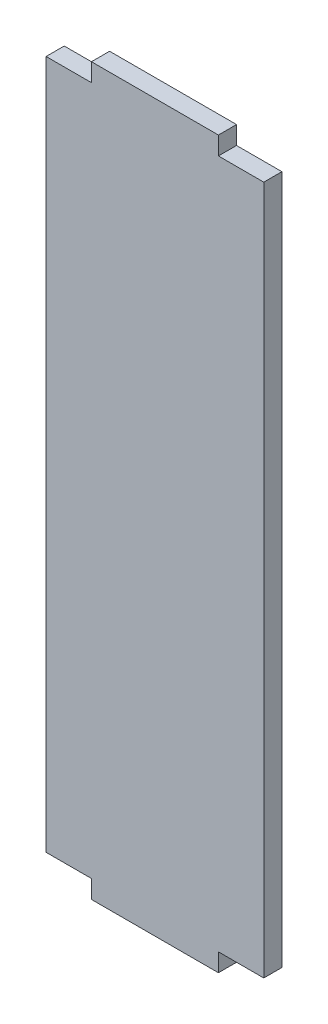
SolidWorks part; units mm, degrees
ref_plane "Plan de face" through (0, 0, 0) normal (0, 0, 1) x (1, 0, 0)
ref_plane "Plan de dessus" through (0, 0, 0) normal (0, 1, 0) x (1, 0, 0)
ref_plane "Plan de droite" through (0, 0, 0) normal (1, 0, 0) x (0, 0, -1)
sketch "Esquisse1" plane through (0, 0, 0) normal (0, 0, 1) x (1, 0, 0)
  line L1 (-30, 95) -> (30, 95)
  line L2 (-30, 95) -> (-30, -95)
  line L3 (-30, -95) -> (30, -95)
  line L4 (30, 95) -> (30, -95)
  line L5 (-30, 95) -> (30, -95) construction
  line L6 (-30, -95) -> (30, 95) construction
  point P0 (0, 0)
  dimension "D1" = 190
  dimension "D2" = 60
extrude "Boss.-Extru.1" add sketch "Esquisse1" along normal blind 5
sketch "Esquisse2" plane through (0, 0, 5) normal (0, 0, 1) x (1, 0, 0)
  line L0 (0, 97.5) -> (0, -97.5) construction
  line L1 (-30, -95) -> (30, -95) construction
  line L2 (-17.5, -100) -> (17.5, -100)
  line L3 (-17.5, -100) -> (-17.5, -95)
  line L4 (-17.5, -95) -> (17.5, -95)
  line L5 (17.5, -100) -> (17.5, -95)
  line L6 (-17.5, -100) -> (17.5, -95) construction
  line L7 (-17.5, -95) -> (17.5, -100) construction
  line L8 (-30, 0) -> (30, 0) construction
  line L9 (-30, 95) -> (-30, -95) construction
  line L10 (30, -95) -> (30, 95) construction
  line L11 (-17.5, 95) -> (17.5, 95)
  line L12 (17.5, 100) -> (17.5, 95)
  line L13 (-17.5, 100) -> (17.5, 100)
  line L14 (-17.5, 100) -> (-17.5, 95)
  point P4 (0, 0)
  dimension "D1" = 5
  dimension "D2" = 35
extrude "Boss.-Extru.2" add sketch "Esquisse2" against normal blind 5
